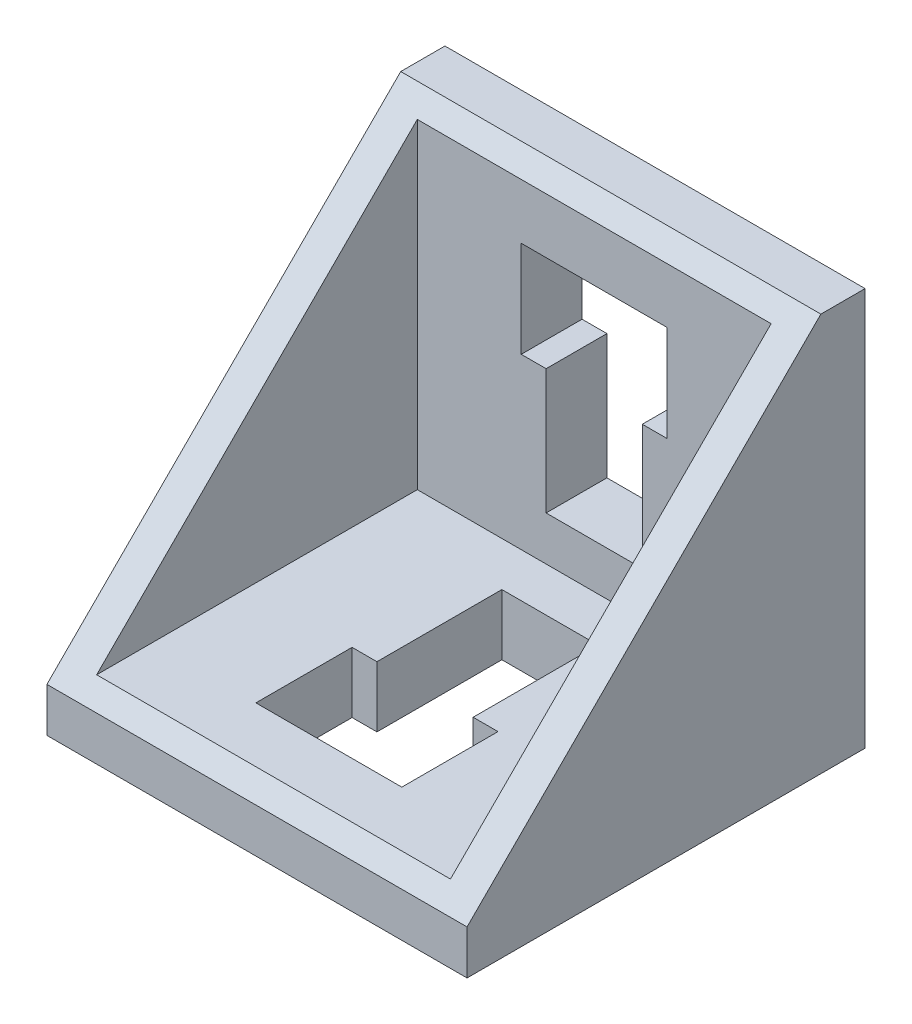
SolidWorks part; units mm, degrees
ref_plane "Piano frontale" through (0, 0, 0) normal (0, 0, 1) x (1, 0, 0)
ref_plane "Piano superiore" through (0, 0, 0) normal (0, 1, 0) x (1, 0, 0)
ref_plane "Piano destro" through (0, 0, 0) normal (1, 0, 0) x (0, 0, -1)
sketch "Schizzo2" plane through (0, 0, 0) normal (1, 0, 0) x (0, 0, -1)
  line L3 (-20, -20) -> (20, -20)
  line L4 (20, 20) -> (20, -20)
  line L6 (-20, -20) -> (20, 20)
  point P0 (0, 0)
  point P2 (28.2841, -11.7159)
  dimension "D1" = 40
  dimension "D2" = 40
extrude "Estrusione-Estrusione1" add sketch "Schizzo2" along normal blind 38
ref_plane "Piano1" through (35, 0, 0) normal (1, 0, 0) x (0, 0, -1)
sketch "Schizzo3" plane through (35, 0, 0) normal (1, 0, 0) x (0, 0, -1)
  line L5 (-20, -14.5) -> (14.5, 20)
  line L7 (14.5, -14.5) -> (14.5, 20)
  line L8 (-20, -14.5) -> (14.5, -14.5)
  line L9 (14.5, -14.5) -> (14.5, 20)
  line L10 (-20, -14.5) -> (14.5, -14.5)
  dimension "D1" = 5.5
extrude "Taglio-Estrusione1" cut sketch "Schizzo3" against normal offset from surface (32 mm away) 3 up to face at (0, -6.6667, -6.6667)
sketch "Schizzo5" plane through (0, 0, 0) normal (1, 0, 0) x (0, 0, -1)
  line L0 (16, 16) -> (20, 16)
  line L1 (20, 20) -> (-20, -20) construction
  line L2 (20, -20) -> (20, 20) construction
  line L3 (20, 16) -> (20, 20)
  line L4 (20, 20) -> (16, 16)
  line L5 (-20, -20) -> (20, -20) construction
  line L6 (-20, -20) -> (-16, -16)
  line L7 (-16, -16) -> (-16, -20)
  line L8 (-16, -20) -> (-20, -20)
  dimension "D1" = 36
  dimension "D2" = 36
extrude "Taglio-Estrusione3" cut sketch "Schizzo5" along normal through all
sketch "Schizzo6" plane through (0, 0, -14.5) normal (0, 0, 1) x (1, 0, 0)
  line L0 (19, -1002.2761) -> (19, 48997.7239) construction
  line L2 (3, 14.5) -> (35, 14.5) construction
  line L3 (25.6, 9.5) -> (12.4, 9.5)
  line L4 (12.4, 9.5) -> (12.4, 0.8)
  line L5 (12.4, 0.8) -> (14.65, 0.8)
  line L6 (14.65, 0.8) -> (14.65, -10.5)
  line L7 (14.65, -10.5) -> (23.35, -10.5)
  line L8 (38, -20) -> (0, -20) construction
  line L9 (23.35, 0.8) -> (23.35, -10.5)
  line L10 (25.6, 0.8) -> (23.35, 0.8)
  line L11 (25.6, 9.5) -> (25.6, 0.8)
  point P4 (19, 14.5)
  point P5 (19, 14.5)
  point P15 (19, -10.5)
  point P18 (19, 9.5)
  dimension "D1" = 6.6
  dimension "D2" = 4.35
  dimension "D3" = 29.5
  dimension "D4" = 20
  dimension "D5" = 8.7
extrude "Taglio-Estrusione4" cut sketch "Schizzo6" against normal through all
sketch "Schizzo8" plane through (0, -14.5, 0) normal (0, 1, 0) x (1, 0, 0)
  line L0 (19, -1010.9757) -> (19, 48989.0243) construction
  line L1 (35, -14.5) -> (3, -14.5) construction
  line L2 (25.6, -9.5) -> (12.4, -9.5)
  line L3 (12.4, -9.5) -> (12.4, -0.8)
  line L4 (12.4, -0.8) -> (14.65, -0.8)
  line L5 (14.65, -0.8) -> (14.65, 10.5)
  line L6 (14.65, 10.5) -> (23.35, 10.5)
  line L7 (38, 20) -> (0, 20) construction
  line L8 (23.35, -0.8) -> (23.35, 10.5)
  line L9 (25.6, -0.8) -> (23.35, -0.8)
  line L10 (25.6, -9.5) -> (25.6, -0.8)
  point P1 (19, -14.5)
  point P14 (19, 10.5)
  point P17 (19, -9.5)
  dimension "D1" = 6.6
  dimension "D2" = 4.35
  dimension "D3" = 29.5
  dimension "D4" = 20
  dimension "D5" = 8.7
extrude "Taglio-Estrusione5" cut sketch "Schizzo8" against normal through all
